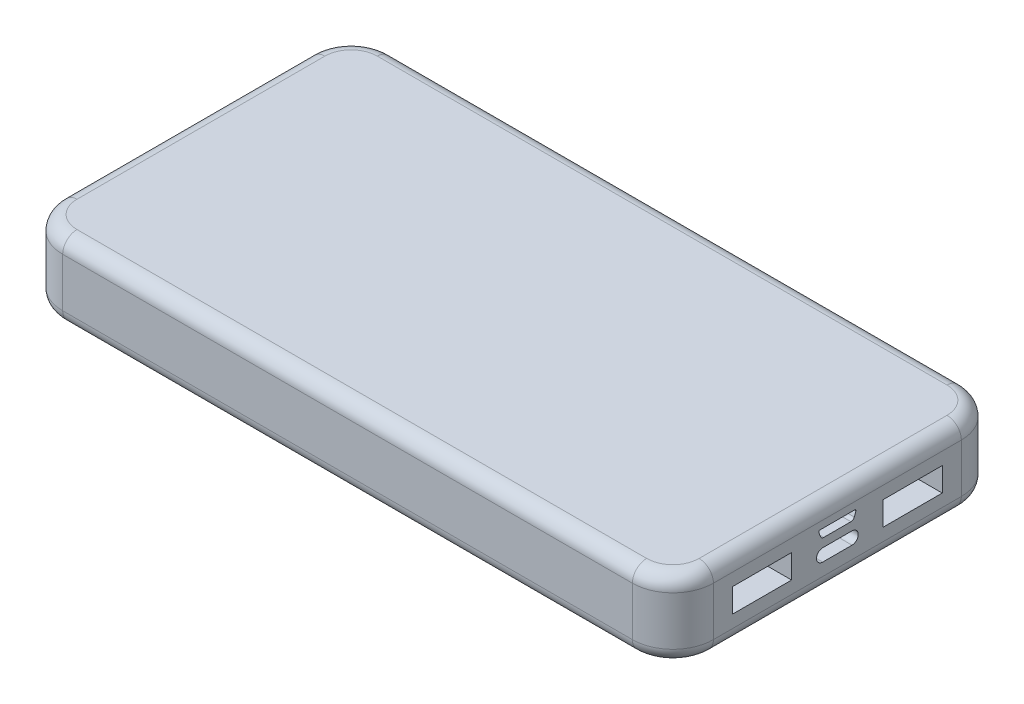
SolidWorks part; units mm, degrees
ref_plane "Front Plane" through (0, 0, 0) normal (0, 0, 1) x (1, 0, 0)
ref_plane "Top Plane" through (0, 0, 0) normal (0, 1, 0) x (1, 0, 0)
ref_plane "Right Plane" through (0, 0, 0) normal (1, 0, 0) x (0, 0, -1)
sketch "Sketch1" plane through (0, 0, 0) normal (0, 1, 0) x (1, 0, 0)
  line L1 (0, 0) -> (136.5, 0)
  line L2 (0, 0) -> (0, -69)
  line L3 (0, -69) -> (136.5, -69)
  line L4 (136.5, 0) -> (136.5, -69)
  dimension "D1" = 136.5
  dimension "D2" = 69
extrude "Boss-Extrude1" add sketch "Sketch1" along normal blind 16.25
fillet "Fillet1" radius 8.5 4 edges at (0, 8.125, 0) (0, 8.125, 69) (136.5, 8.125, 0) (136.5, 8.125, 69)
fillet "Fillet2" radius 3 16 edges at (2.4896, 0, 66.5104) (0, 0, 34.5) (2.4896, 0, 2.4896) (68.25, 0, 0) (134.0104, 0, 2.4896) (136.5, 0, 34.5) (134.0104, 0, 66.5104) (2.4896, 16.25, 66.5104) (0, 16.25, 34.5) (2.4896, 16.25, 2.4896) (68.25, 16.25, 0) (134.0104, 16.25, 2.4896) (136.5, 16.25, 34.5) (134.0104, 16.25, 66.5104) (68.25, 0, 69) (68.25, 16.25, 69)
sketch "Sketch2" plane through (136.5, 0, 0) normal (1, 0, 0) x (0, 0, -1)
  line L0 (-69, 8.125) -> (0, 8.125) construction
  line L1 (-24.9, 10.625) -> (-12.5, 10.625)
  line L2 (-24.9, 10.625) -> (-24.9, 5.625)
  line L3 (-24.9, 5.625) -> (-12.5, 5.625)
  line L4 (-12.5, 10.625) -> (-12.5, 5.625)
  line L5 (-56.5, 10.625) -> (-44.1, 10.625)
  line L6 (-56.5, 10.625) -> (-56.5, 5.625)
  line L7 (-56.5, 5.625) -> (-44.1, 5.625)
  line L8 (-44.1, 10.625) -> (-44.1, 5.625)
  line L9 (-69, 3) -> (-69, 13.25) construction
  line L10 (0, 13.25) -> (0, 3) construction
  point P14 (-56.5, 8.125)
  point P15 (-24.9, 8.125)
  dimension "D1" = 12.4
  dimension "D2" = 5
  dimension "D3" = 12.5
  dimension "D4" = 12.5
extrude "Cut-Extrude1" cut sketch "Sketch2" against normal blind 12
sketch "Sketch3" plane through (136.5, 0, 0) normal (1, 0, 0) x (0, 0, -1)
  line L0 (-37.575, 5.625) -> (-31.425, 5.625)
  line L1 (-31.425, 8.225) -> (-37.575, 8.225)
  line L2 (-38.875, 8.7958) -> (-38.875, 5.0542) construction
  line L3 (-30.125, 8.6558) -> (-30.125, 5.1942) construction
  line L4 (-34.5, 13.25) -> (-34.5, 3) construction
  line L5 (-8.5, 13.25) -> (-60.5, 13.25) construction
  line L6 (-60.5, 3) -> (-8.5, 3) construction
  line L7 (-56.5, 5.625) -> (-44.1, 5.625) construction
  arc A0 (-31.425, 5.625) -> (-31.425, 8.225) centre (-31.425, 6.925) ccw
  arc A1 (-37.575, 8.225) -> (-37.575, 5.625) centre (-37.575, 6.925) ccw
  point P10 (-38.875, 6.925)
  point P13 (-30.125, 6.925)
  point P19 (-34.5, 8.225)
  dimension "D1" = 8.75
  dimension "D2" = 2.6
extrude "Cut-Extrude2" cut sketch "Sketch3" against normal blind 5
sketch "Sketch4" plane through (136.5, 0, 0) normal (1, 0, 0) x (0, 0, -1)
  line L0 (-37.3449, 10) -> (-31.6551, 10)
  line L1 (-30.9503, 10.4935) -> (-30.6151, 11.4145)
  line L2 (-30.85, 11.75) -> (-38.15, 11.75)
  line L3 (-38.3849, 11.4145) -> (-38.0497, 10.4935)
  line L4 (-34.5, 8.225) -> (-34.5, 13.25) construction
  line L5 (-31.425, 8.225) -> (-37.575, 8.225) construction
  line L6 (-8.5, 13.25) -> (-60.5, 13.25) construction
  line L7 (-60.5, 16.25) -> (-8.5, 16.25) construction
  arc A0 (-30.6151, 11.4145) -> (-30.85, 11.75) centre (-30.85, 11.5) ccw
  arc A1 (-38.15, 11.75) -> (-38.3849, 11.4145) centre (-38.15, 11.5) ccw
  arc A2 (-31.6551, 10) -> (-30.9503, 10.4935) centre (-31.6551, 10.75) ccw
  arc A3 (-37.3449, 10) -> (-38.0497, 10.4935) centre (-37.3449, 10.75) cw
  point P18 (-34.5, 11.75)
  dimension "D1" = 0.25
  dimension "D2" = 0.75
  dimension "D3" = 110
  dimension "D4" = 110
  dimension "D5" = 1.75
  dimension "D6" = 4.5
  dimension "D7" = 7.3
extrude "Cut-Extrude3" cut sketch "Sketch4" against normal blind 4
